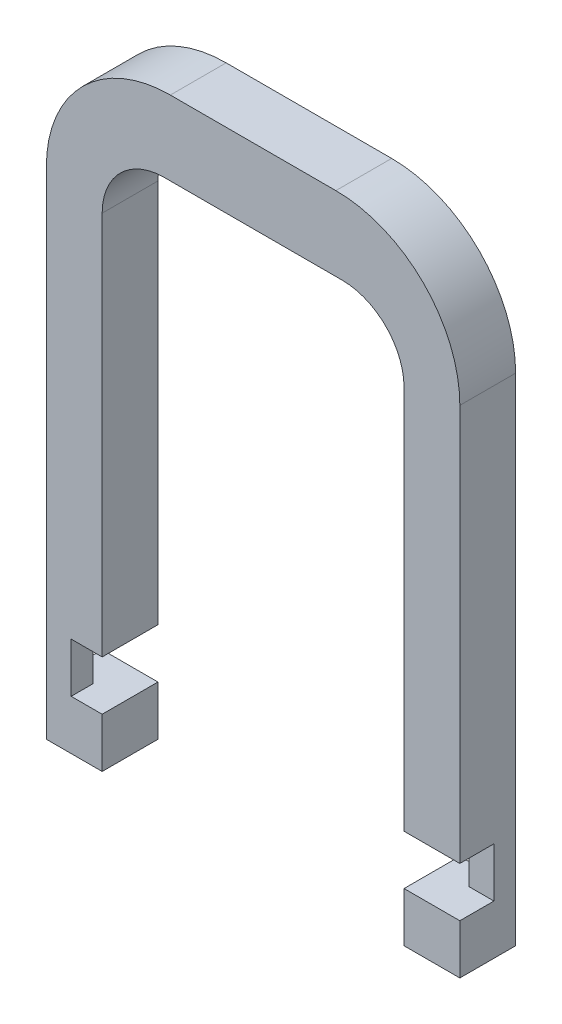
SolidWorks part; units mm, degrees
ref_plane "Front Plane" through (0, 0, 0) normal (0, 0, 1) x (1, 0, 0)
ref_plane "Top Plane" through (0, 0, 0) normal (0, 1, 0) x (1, 0, 0)
ref_plane "Right Plane" through (0, 0, 0) normal (1, 0, 0) x (0, 0, -1)
sketch "Sketch1" plane through (0, 0, 0) normal (0, 1, 0) x (1, 0, 0)
  line L1 (-20.641, 2.5) -> (-16.141, 2.5)
  line L2 (-20.641, 2.5) -> (-20.641, -2)
  line L3 (-20.641, -2) -> (-16.141, -2)
  line L4 (-16.141, 2.5) -> (-16.141, -2)
  line L5 (-20.641, 2.5) -> (-16.141, -2) construction
  line L6 (-20.641, -2) -> (-16.141, 2.5) construction
  line L7 (8.209, 2.5) -> (12.709, 2.5)
  line L8 (8.209, 2.5) -> (8.209, -2)
  line L9 (8.209, -2) -> (12.709, -2)
  line L10 (12.709, 2.5) -> (12.709, -2)
  line L11 (8.209, 2.5) -> (12.709, -2) construction
  line L12 (8.209, -2) -> (12.709, 2.5) construction
  point P0 (-18.391, 0.25)
  point P5 (10.459, 0.25)
  dimension "D1" = 4.5
  dimension "D2" = 4.5
  dimension "D3" = 4.5
  dimension "D4" = 4.5
  dimension "D5" = 24.35
  dimension "D6" = 0
extrude "Boss-Extrude1" add sketch "Sketch1" along normal blind 50
sketch "Sketch2" plane through (8.209, 0, 0) normal (-1, 0, 0) x (0, 0, 1)
  line L0 (2, 50) -> (2, 0) construction
  line L1 (-2.5, 50) -> (2, 50)
  line L2 (-2.5, 50) -> (-2.5, 44)
  line L3 (-2.5, 44) -> (2, 44)
  line L4 (2, 50) -> (2, 44)
  dimension "D1" = 6
extrude "Boss-Extrude2" add sketch "Sketch2" along normal blind 25
fillet "Fillet1" radius 10 2 edges at (-20.641, 50, -0.25) (12.709, 50, -0.25)
fillet "Fillet2" radius 5 2 edges at (-16.141, 44, -0.25)
sketch "Sketch5" plane through (0, 0, 2) normal (0, 0, 1) x (1, 0, 0)
  line L0 (8.209, 39) -> (8.209, 0) construction
  line L1 (8.209, 8) -> (12.709, 8)
  line L2 (8.209, 8) -> (8.209, 4)
  line L3 (8.209, 4) -> (12.709, 4)
  line L4 (12.709, 8) -> (12.709, 4)
  line L5 (12.709, 40) -> (12.709, 0) construction
  line L6 (8.209, 0) -> (12.709, 0) construction
  dimension "D1" = 4
  dimension "D2" = 4
extrude "Cut-Extrude3" cut sketch "Sketch5" against normal blind 2.75
sketch "Sketch6" plane through (0, 0, -2.5) normal (0, 0, -1) x (-1, 0, 0)
  line L0 (16.141, 39) -> (16.141, 0) construction
  line L1 (16.141, 8) -> (20.641, 8)
  line L2 (16.141, 8) -> (16.141, 4)
  line L3 (16.141, 4) -> (20.641, 4)
  line L4 (20.641, 8) -> (20.641, 4)
  line L5 (20.641, 40) -> (20.641, 0) construction
  line L6 (16.141, 0) -> (20.641, 0) construction
  dimension "D1" = 4
  dimension "D2" = 4
extrude "Cut-Extrude4" cut sketch "Sketch6" against normal blind 2.75
sketch "Sketch3" plane through (8.209, 0, 0) normal (-1, 0, 0) x (0, 0, 1)
  line L0 (-2.5, 39) -> (-2.5, 0) construction
  line L1 (-2.5, 4) -> (2, 4)
  line L2 (-2.5, 4) -> (-2.5, 8)
  line L3 (-2.5, 8) -> (2, 8)
  line L4 (2, 4) -> (2, 8)
  line L5 (2, 39) -> (2, 8) construction
  line L6 (-2.5, 0) -> (2, 0) construction
  dimension "D1" = 8
  dimension "D2" = 4
extrude "Cut-Extrude1" cut sketch "Sketch3" against normal blind 2.5
sketch "Sketch4" plane through (-16.141, 0, 0) normal (1, 0, 0) x (0, 0, -1)
  line L0 (-2, 39) -> (-2, 0) construction
  line L1 (-2, 8) -> (2.5, 8)
  line L2 (-2, 8) -> (-2, 4)
  line L3 (-2, 4) -> (2.5, 4)
  line L4 (2.5, 8) -> (2.5, 4)
  line L5 (2.5, 39) -> (2.5, 8) construction
  line L6 (-2, 0) -> (2.5, 0) construction
  dimension "D1" = 4
  dimension "D2" = 4
extrude "Cut-Extrude2" cut sketch "Sketch4" against normal blind 2.5
